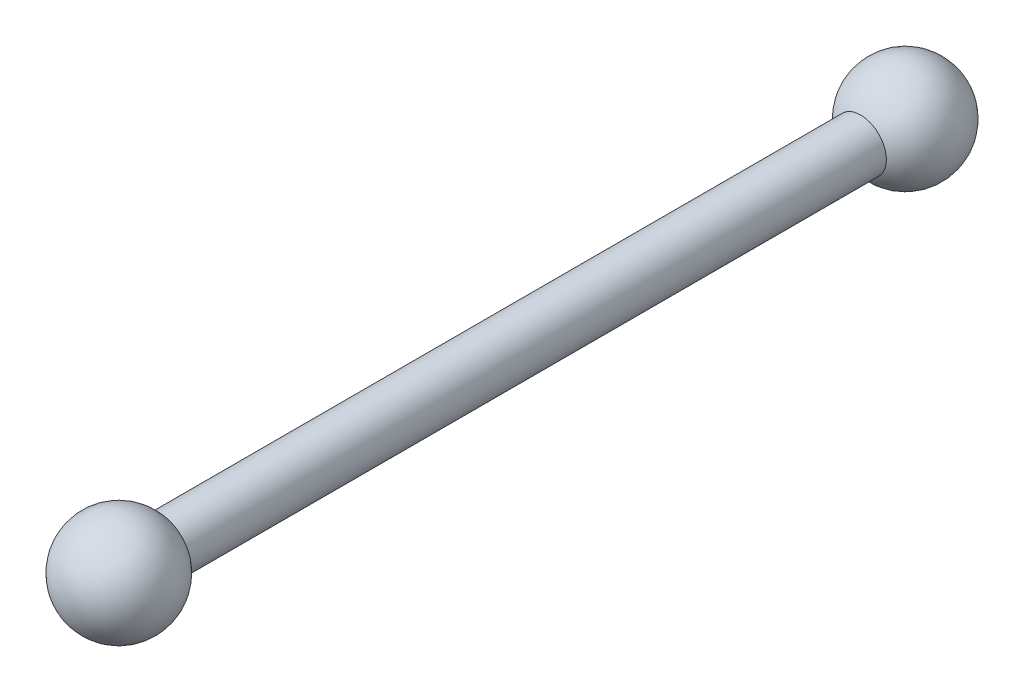
SolidWorks part; units mm, degrees
ref_plane "Front Plane" through (0, 0, 0) normal (0, 0, 1) x (1, 0, 0)
ref_plane "Top Plane" through (0, 0, 0) normal (0, 1, 0) x (1, 0, 0)
ref_plane "Right Plane" through (0, 0, 0) normal (1, 0, 0) x (0, 0, -1)
sketch "Sketch1" plane through (0, 0, 0) normal (0, 0, 1) x (1, 0, 0)
  circle A0 centre (0, 0) radius 2
  dimension "D1" = 4
extrude "Boss-Extrude1" add sketch "Sketch1" against normal blind 55
ref_plane "Plane1" through (0, 0, 3) normal (0, 0, 1) x (1, 0, 0)
sketch "Sketch2" plane through (0, 0, 3) normal (0, 0, 1) x (1, 0, 0)
  line L0 (0, 4) -> (0, -4) construction
  line L1 (0, 4) -> (0, -4)
  arc A1 (0, -4) -> (0, 4) centre (0, 0) ccw
  dimension "D1" = 8
revolve "Revolve1" add sketch "Sketch2" angle 360 about L0
ref_plane "Plane2" through (0, 0, -27.5) normal (0, 0, 1) x (1, 0, 0)
mirror "Mirror2" about plane through (0, 0, -27.5) normal (0, 0, 1) of "Revolve1"
